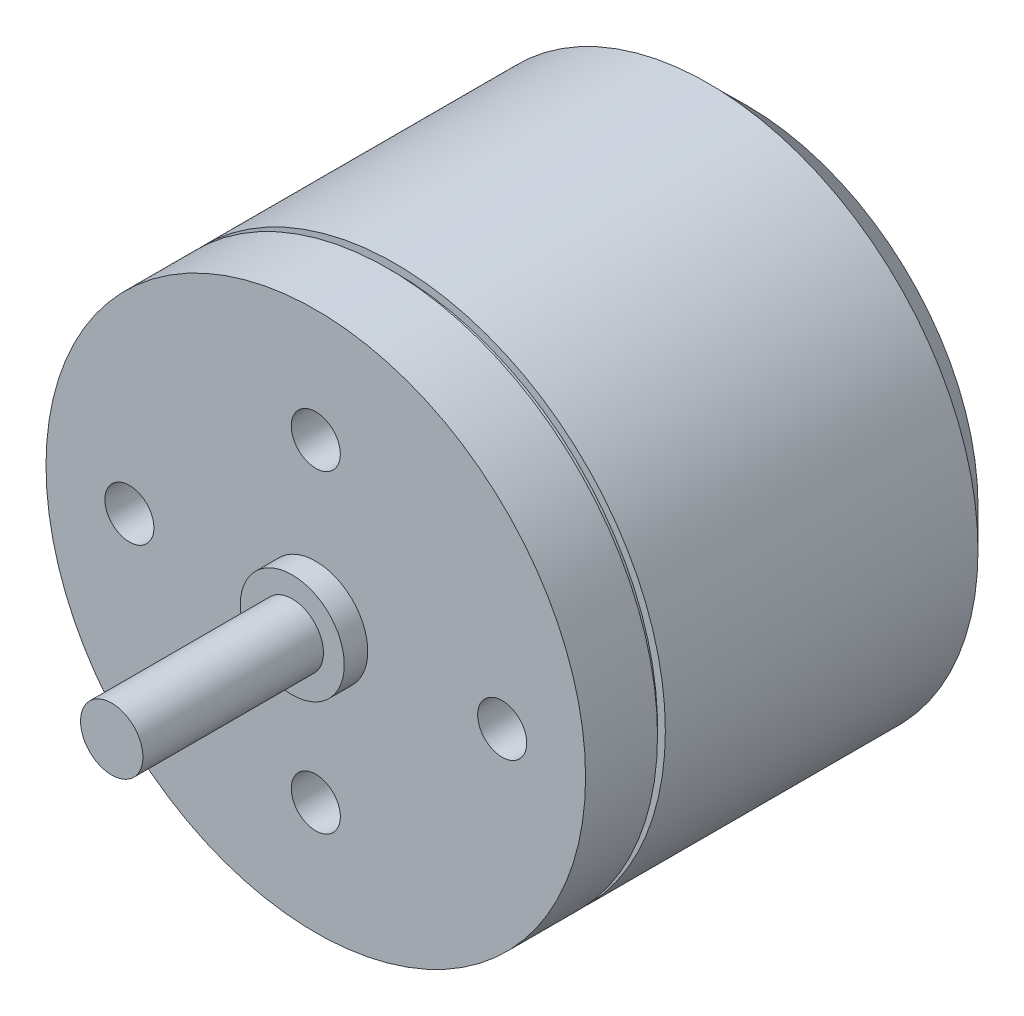
SolidWorks part; units mm, degrees
ref_plane "Front Plane" through (0, 0, 0) normal (0, 0, 1) x (1, 0, 0)
ref_plane "Top Plane" through (0, 0, 0) normal (0, 1, 0) x (1, 0, 0)
ref_plane "Right Plane" through (0, 0, 0) normal (1, 0, 0) x (0, 0, -1)
sketch "Sketch1" plane through (0, 0, 0) normal (0, 1, 0) x (1, 0, 0)
  line L0 (0, 0) -> (0, 42.7092) construction
  line L1 (0, 0) -> (50.0896, 0) construction
  line L2 (13.75, 0) -> (13.75, 3.6667)
  line L3 (13.75, 22) -> (0, 22)
  line L4 (0, 22) -> (0, 0)
  line L5 (0, 0) -> (13.75, 0)
  line L6 (13.75, 4.0667) -> (13.75, 22)
  line L7 (13.75, 4.0667) -> (13.35, 4.0667)
  line L8 (13.35, 4.0667) -> (13.35, 3.6667)
  line L9 (13.35, 3.6667) -> (13.75, 3.6667)
  dimension "D1" = 0.4
  dimension "D2" = 13.75
  dimension "D3" = 3.6667
  dimension "D4" = 22
revolve "Revolve1" add sketch "Sketch1" angle 360 about L4
sketch "Sketch2" plane through (0, 0, 0) normal (0, 0, 1) x (1, 0, 0)
  line L0 (0, 0) -> (-4.9537, 0) construction
  line L1 (0, 0) -> (0, -4.7938) construction
  circle A0 centre (9.5, 0) radius 1.25
  circle A1 centre (0, 8) radius 1.25
  circle A2 centre (0, -8) radius 1.25
  circle A3 centre (-9.5, 0) radius 1.25
  dimension "D1" = 2.5
  dimension "D2" = 2.5
  dimension "D3" = 9.5
  dimension "D4" = 8
extrude "Cut-Extrude1" cut sketch "Sketch2" against normal blind 2
sketch "Sketch3" plane through (0, 0, -22) normal (0, 0, -1) x (-1, 0, 0)
  circle A0 centre (6, 0) radius 1.25
  circle A1 centre (0, -6) radius 1.25
  circle A2 centre (-6, 0) radius 1.25
  circle A3 centre (0, 6) radius 1.25
  point P2 (0, 0)
  point P13 (0, 0)
  dimension "D1" = 2.5
  dimension "D2" = 6
  dimension "D3" = 4
extrude "Cut-Extrude2" cut sketch "Sketch3" against normal blind 2
sketch "Sketch4" plane through (0, 0, 0) normal (0, 0, 1) x (1, 0, 0)
  circle A0 centre (0, 0) radius 2.65
  dimension "D1" = 5.3
extrude "Boss-Extrude1" add sketch "Sketch4" along normal blind 1.2
sketch "Sketch5" plane through (0, 0, 1.2) normal (0, 0, 1) x (1, 0, 0)
  circle A0 centre (0, 0) radius 1.59
  dimension "D1" = 3.18
extrude "Boss-Extrude2" add sketch "Sketch5" along normal blind 9.2
chamfer "Chamfer1" distance 2 angle 45 1 edges at (-13.75, 0, -22)
equation "\"D3@Sketch1\"=\"D4@Sketch1\"/6"
